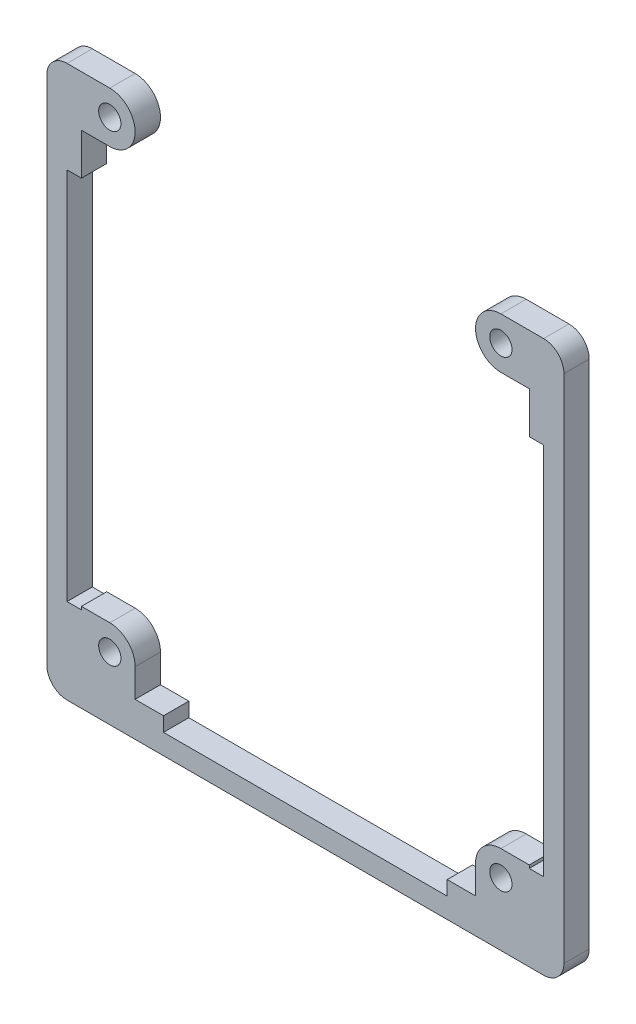
SolidWorks part; units mm, degrees
ref_plane "Front Plane" through (0, 0, 0) normal (0, 0, 1) x (1, 0, 0)
ref_plane "Top Plane" through (0, 0, 0) normal (0, 1, 0) x (1, 0, 0)
ref_plane "Right Plane" through (0, 0, 0) normal (1, 0, 0) x (0, 0, -1)
sketch "Sketch1" plane through (0, 0, 0) normal (0, 0, 1) x (1, 0, 0)
  line L1 (0, 6.35) -> (0, 53.213) construction
  line L2 (1.8034, 6.35) -> (1.8034, 53.213) construction
  line L3 (1.8034, 6.35) -> (0, 6.35) construction
  line L4 (-57.9374, 6.35) -> (-56.134, 6.35) construction
  line L7 (-57.9374, 53.213) -> (-56.134, 53.213) construction
  line L8 (-45.847, -1.8034) -> (-45.847, 0) construction
  line L9 (-10.287, 0) -> (-45.847, 0) construction
  line L10 (-10.287, -1.8034) -> (-45.847, -1.8034) construction
  line L11 (-10.287, -1.8034) -> (-10.287, 0) construction
  line L12 (0, 53.213) -> (1.8034, 53.213)
  line L13 (0, 6.35) -> (0, 53.213)
  line L14 (1.8034, 6.35) -> (1.8034, 53.213)
  line L15 (1.8034, 6.35) -> (0, 6.35)
  line L16 (-57.9374, 6.35) -> (-56.134, 6.35)
  line L17 (-57.9374, 6.35) -> (-57.9374, 53.213)
  line L18 (-56.134, 6.35) -> (-56.134, 53.213)
  line L19 (-57.9374, 53.213) -> (-56.134, 53.213)
  line L20 (-45.847, -1.8034) -> (-45.847, 0)
  line L21 (-10.287, 0) -> (-45.847, 0)
  line L22 (-10.287, -1.8034) -> (-45.847, -1.8034)
  line L23 (-10.287, -1.8034) -> (-10.287, 0)
  line L24 (-28.067, 0) -> (-28.067, 55.1636) construction
  line L25 (-3.556, 61.595) -> (-3.556, 3.556) construction
  line L26 (-52.578, 61.595) -> (-52.578, 3.556) construction
  line L27 (-52.578, 58.42) -> (-56.134, 58.42)
  line L28 (-57.9374, 64.77) -> (1.8034, 64.77)
  line L29 (-60.4774, 62.23) -> (-60.4774, -1.8034)
  line L30 (-57.9374, -4.3434) -> (1.8034, -4.3434)
  line L31 (4.3434, 62.23) -> (4.3434, -1.8034)
  line L33 (-56.134, 58.42) -> (-56.134, 53.213)
  line L34 (-52.578, 6.731) -> (-56.134, 6.731)
  line L35 (-49.403, 3.556) -> (-49.403, 0)
  line L36 (-45.847, 0) -> (-57.9374, 0) construction
  line L37 (-49.403, 0) -> (-45.847, 0)
  line L38 (-10.287, 0) -> (-6.731, 0)
  line L39 (1.8034, 0) -> (-10.287, 0) construction
  line L40 (-6.731, 0) -> (-6.731, 3.556)
  line L41 (-3.556, 6.731) -> (0, 6.731)
  line L42 (-3.556, 58.42) -> (0, 58.42)
  line L44 (0, 58.42) -> (0, 53.213)
  line L46 (-56.134, 6.731) -> (-56.134, 6.35)
  line L47 (0, 6.35) -> (0, 6.731)
  line L48 (-6.731, 0) -> (-10.287, 0)
  circle A0 centre (-3.556, 3.556) radius 1.397
  circle A1 centre (-3.556, 61.595) radius 1.397
  circle A2 centre (-52.578, 61.595) radius 1.397
  circle A3 centre (-52.578, 3.556) radius 1.397
  circle A4 centre (-52.578, 61.595) radius 3.175
  circle A5 centre (-52.578, 3.556) radius 3.175
  circle A6 centre (-3.556, 61.595) radius 3.175
  circle A7 centre (-3.556, 3.556) radius 3.175
  arc A8 (-60.4774, -1.8034) -> (-57.9374, -4.3434) centre (-57.9374, -1.8034) ccw
  arc A9 (1.8034, -4.3434) -> (4.3434, -1.8034) centre (1.8034, -1.8034) ccw
  arc A10 (1.8034, 64.77) -> (4.3434, 62.23) centre (1.8034, 62.23) cw
  arc A11 (-57.9374, 64.77) -> (-60.4774, 62.23) centre (-57.9374, 62.23) ccw
  dimension "D1" = 2.159
  dimension "D2" = 2.794
  dimension "D3" = 2.159
  dimension "D4" = 55.245
  dimension "D5" = 6.35
  dimension "D9" = 2.54
  dimension "D6" = 2.54
  dimension "D7" = 2.54
  dimension "D8" = 2.54
extrude "Boss-Extrude1" add sketch "Sketch1" along normal blind 3.175
